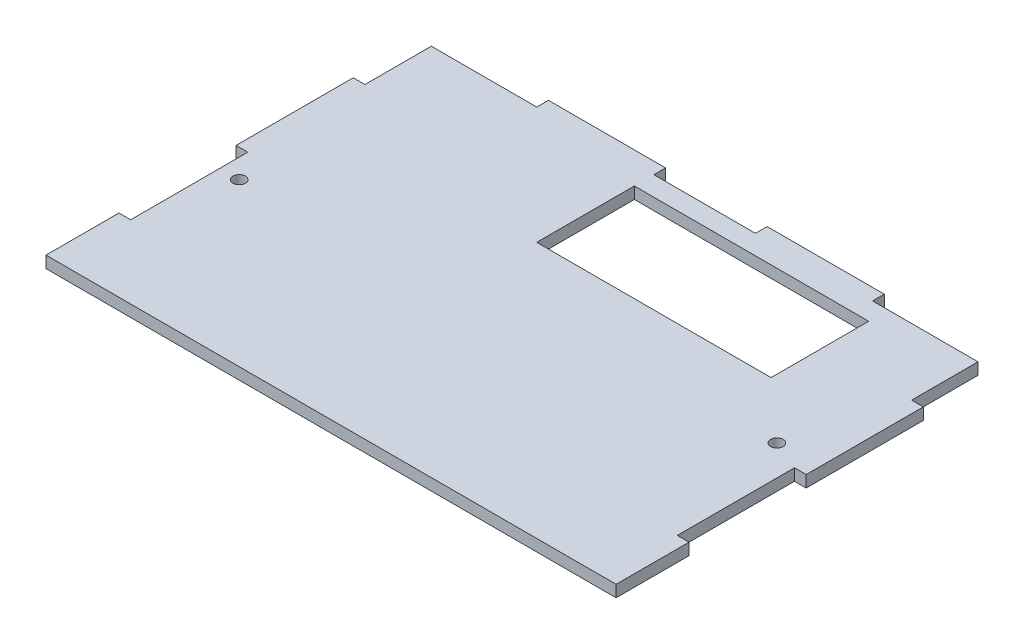
SolidWorks part; units mm, degrees
ref_plane "Front Plane" through (0, 0, 0) normal (0, 0, 1) x (1, 0, 0)
ref_plane "Top Plane" through (0, 0, 0) normal (0, 1, 0) x (1, 0, 0)
ref_plane "Right Plane" through (0, 0, 0) normal (1, 0, 0) x (0, 0, -1)
other "Configuration Table"
sketch "Sketch1" plane through (0, 0, 0) normal (0, 1, 0) x (1, 0, 0)
  line L1 (73, -80.5) -> (-73, -80.5)
  line L2 (73, -80.5) -> (73, 80.5)
  line L3 (73, 80.5) -> (-73, 80.5)
  line L4 (-73, -80.5) -> (-73, 80.5)
  line L5 (73, -80.5) -> (-73, 80.5) construction
  line L6 (73, 80.5) -> (-73, -80.5) construction
  point P0 (0, 0)
  dimension "D1" = 146
  dimension "D2" = 161
extrude "Boss-Extrude1" add sketch "Sketch1" along normal blind 3
sketch "Sketch2" plane through (0, 3, 0) normal (0, 1, 0) x (1, 0, 0)
  line L0 (73, 80.5) -> (-73, 80.5) construction
  line L5 (-13, 80.5) -> (13, 80.5)
  line L6 (-13, 80.5) -> (-13, 77.5)
  line L7 (-13, 77.5) -> (13, 77.5)
  line L8 (13, 80.5) -> (13, 77.5)
  line L9 (73, -80.5) -> (73, 80.5) construction
  line L14 (-70, 30.5) -> (-70, 0.5)
  line L16 (-73, 80.5) -> (-73, 60.5)
  line L17 (-73, 60.5) -> (-70, 60.5)
  line L18 (-70, 77.5) -> (-70, 60.5)
  line L23 (-73, 80.5) -> (-43, 80.5)
  line L25 (73, 80.5) -> (73, 60.5)
  line L26 (73, 60.5) -> (70, 60.5)
  line L27 (70, 77.5) -> (70, 60.5)
  line L36 (-43, 80.5) -> (-43, 77.5)
  line L37 (-43, 77.5) -> (-70, 77.5)
  line L38 (73, 80.5) -> (43, 80.5)
  line L39 (43, 80.5) -> (43, 77.5)
  line L40 (43, 77.5) -> (70, 77.5)
  line L42 (-70, 30.5) -> (-73, 30.5)
  line L43 (-73, 80.5) -> (-73, -80.5) construction
  line L44 (-73, 30.5) -> (-73, 0.5)
  line L45 (-73, 0.5) -> (-70, 0.5)
  line L46 (70, 0.5) -> (70, 30.5)
  line L47 (70, 30.5) -> (73, 30.5)
  line L48 (73, 30.5) -> (73, 0.5)
  line L49 (73, 0.5) -> (70, 0.5)
  line L54 (-70, -59.5) -> (-70, -29.5)
  line L55 (-70, -29.5) -> (-73, -29.5)
  line L56 (-73, -29.5) -> (-73, -59.5)
  line L57 (-73, -59.5) -> (-70, -59.5)
  line L63 (-70, -79.5) -> (-73, -79.5)
  line L64 (-73, -79.5) -> (-73, -80.5)
  line L65 (-73, -80.5) -> (-43, -80.5)
  line L66 (-73, -80.5) -> (73, -80.5) construction
  line L67 (70, -59.5) -> (70, -29.5)
  line L68 (70, -29.5) -> (73, -29.5)
  line L69 (73, -29.5) -> (73, -59.5)
  line L70 (73, -59.5) -> (70, -59.5)
  line L72 (70, -79.5) -> (73, -79.5)
  line L73 (73, -79.5) -> (73, -80.5)
  line L74 (73, -80.5) -> (70, -80.5)
  line L75 (-70, -79.5) -> (-70, -77.5)
  line L76 (-70, -77.5) -> (-43, -77.5)
  line L77 (-43, -77.5) -> (-43, -80.5)
  line L78 (-13, -80.5) -> (-13, -77.5)
  line L79 (-13, -77.5) -> (13, -77.5)
  line L80 (13, -77.5) -> (13, -80.5)
  line L81 (13, -80.5) -> (-13, -80.5)
  line L82 (43, -80.5) -> (43, -77.5)
  line L83 (43, -77.5) -> (70, -77.5)
  line L84 (70, -77.5) -> (70, -79.5)
  line L85 (43, -80.5) -> (70, -80.5)
  line L87 (-13, 72.5) -> (47, 72.5)
  line L88 (-13, 72.5) -> (-13, 47.5)
  line L89 (-13, 47.5) -> (47, 47.5)
  line L90 (47, 72.5) -> (47, 47.5)
  dimension "D2" = 26
  dimension "D3" = 30
  dimension "D4" = 3
  dimension "D5" = 20
  dimension "D6" = 3
  dimension "D7" = 30
  dimension "D8" = 30
  dimension "D9" = 30
  dimension "D10" = 3
  dimension "D11" = 3
  dimension "D12" = 30
  dimension "D13" = 30
  dimension "D14" = 20
  dimension "D15" = 30
  dimension "D16" = 3
  dimension "D17" = 3
  dimension "D18" = 5
  dimension "D19" = 25
  dimension "D20" = 60
extrude "Cut-Extrude1" cut sketch "Sketch2" against normal blind 3
sketch "Sketch3" plane through (0, 0, 0) normal (0, -1, 0) x (-1, 0, 0)
  line L0 (-73, -18.18) -> (-73, -80.5)
  line L1 (-73, -80.5) -> (73, -80.5)
  line L2 (73, -80.5) -> (73, -18.18)
  line L3 (73, -18.18) -> (-73, -18.18)
  line L5 (-73, -29.5) -> (-70, -29.5) construction
  dimension "D1" = 11.32
extrude "Cut-Extrude2" cut sketch "Sketch3" against normal blind 10
sketch "Sketch4" plane through (0, 0, 0) normal (0, -1, 0) x (1, 0, 0)
  line L0 (43, -80.5) -> (13, -80.5) construction
  line L1 (73, -30.5) -> (73, -60.5) construction
  line L2 (-13, -80.5) -> (-43, -80.5) construction
  line L3 (-70, -0.5) -> (-70, -30.5) construction
  circle A0 centre (62.25, -33.75) radius 1.6
  circle A1 centre (-65, -23.3) radius 1.6
  dimension "D1" = 46.75
  dimension "D2" = 10.75
  dimension "D3" = 57.2
  dimension "D4" = 5
extrude "Cut-Extrude3" cut sketch "Sketch4" against normal blind 10
